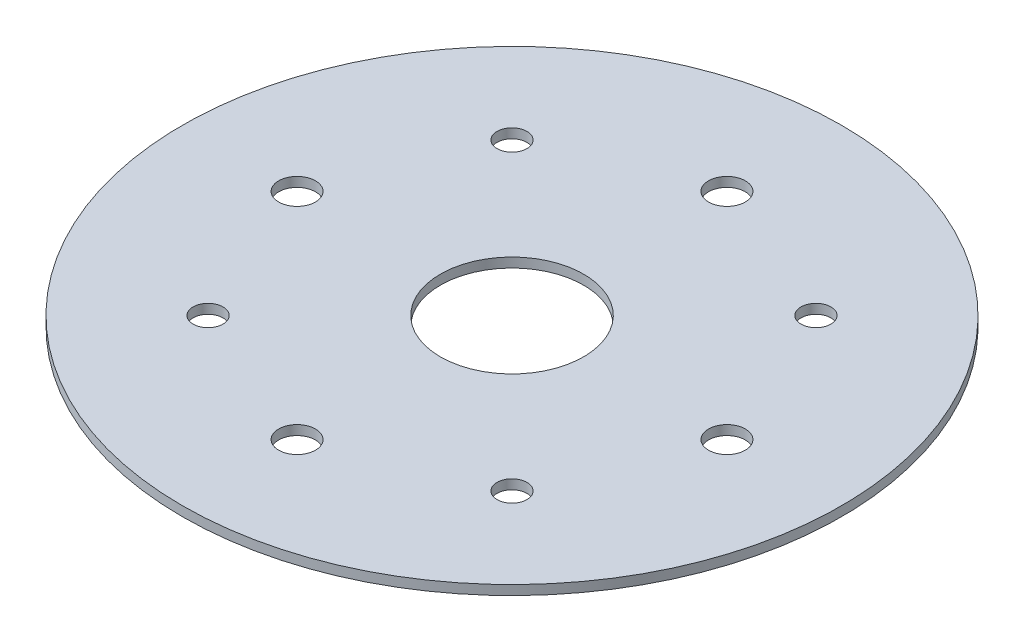
SolidWorks part; units mm, degrees
ref_plane "Front Plane" through (0, 0, 0) normal (0, 0, 1) x (1, 0, 0)
ref_plane "Top Plane" through (0, 0, 0) normal (0, 1, 0) x (1, 0, 0)
ref_plane "Right Plane" through (0, 0, 0) normal (1, 0, 0) x (0, 0, -1)
sketch "Sketch1" plane through (0, 0, 0) normal (0, 1, 0) x (1, 0, 0)
  circle A0 centre (22.5, 0) radius 1.925
  circle A1 centre (0, -22.5) radius 1.925
  circle A2 centre (-22.5, 0) radius 1.925
  circle A3 centre (0, 22.5) radius 1.925
  circle A4 centre (0, 0) radius 34.5
  circle A5 centre (15.9099, 15.9099) radius 1.5635
  circle A6 centre (-15.9099, 15.9099) radius 1.5635
  circle A7 centre (-15.9099, -15.9099) radius 1.5635
  circle A8 centre (15.9099, -15.9099) radius 1.5635
  circle A9 centre (0, 0) radius 7.5
  text T0 "SOLIDWORKS Educational Product." font "SWTXT" height 4.8336
  text T1 "For Instructional Use Only." font "SWTXT" height 4.8336
extrude "Boss-Extrude1" add sketch "Sketch1" along normal blind 1 contours A4 A9 A8 A7 A6 A5 A0 A1 A2 A3
